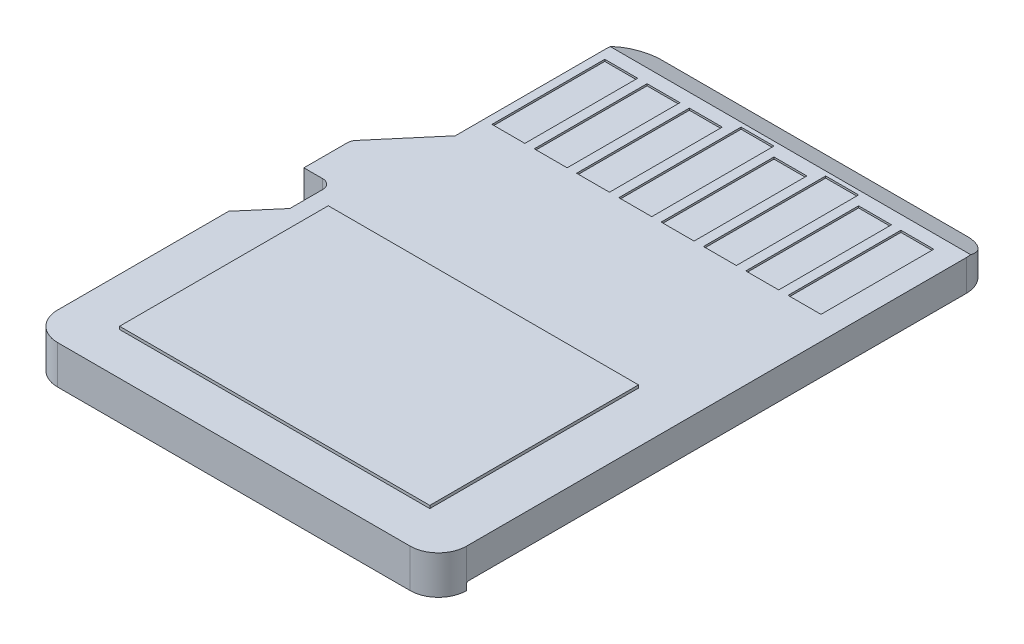
SolidWorks part; units mm, degrees
ref_plane "Front Plane" through (0, 0, 0) normal (0, 0, 1) x (1, 0, 0)
ref_plane "Top Plane" through (0, 0, 0) normal (0, 1, 0) x (1, 0, 0)
ref_plane "Right Plane" through (0, 0, 0) normal (1, 0, 0) x (0, 0, -1)
ref_plane "Plane1" through (1.2954, 0, 0) normal (-1, 0, 0) x (0, -1, 0)
sketch "Sketch1" plane through (1.2954, 0, 0) normal (-1, 0, 0) x (0, -1, 0)
  line L0 (-0.8382, 0) -> (-0.8382, -14.3917)
  line L1 (-0.8382, -14.3917) -> (-0.5842, -15.0267)
  line L2 (-0.5842, -15.0267) -> (0, -15.0267)
  line L3 (0, -15.0267) -> (0, 0)
  line L4 (0, 0) -> (-0.8382, 0)
extrude "Boss-Extrude1" add sketch "Sketch1" against normal blind 9.7536
sketch "Sketch2" plane through (1.2954, 0, 0) normal (-1, 0, 0) x (0, 0, 1)
  line L0 (0, 0) -> (-8.6868, 0)
  line L1 (-8.6868, 0) -> (-8.6868, 0.8382)
  line L2 (-8.6868, 0.8382) -> (0, 0.8382)
  line L3 (0, 0.8382) -> (0, 0)
extrude "Boss-Extrude2" add sketch "Sketch2" along normal blind 1.2954
sketch "Sketch3" plane through (0, 0, 0) normal (0, -1, 0) x (1, 0, 0)
  line L0 (0, -0.762) -> (0, 0)
  line L1 (0, 0) -> (11.049, 0)
  line L2 (11.049, 0) -> (11.049, -0.762)
  arc A0 (11.049, -0.762) -> (0, -0.762) centre (5.5245, 14.8745) cw
extrude "Boss-Extrude3" add sketch "Sketch3" along normal blind 0.2032
sketch "Sketch4" plane through (0, 0.8382, 0) normal (0, 1, 0) x (-1, 0, 0)
  line L0 (0, -5.3848) -> (-0.762, -5.3848)
  line L1 (-0.762, -5.3848) -> (-0.762, -7.4168)
  line L2 (-0.762, -7.4168) -> (0, -7.4168)
  line L3 (0, -7.4168) -> (0, -5.3848)
extrude "Cut-Extrude1" cut sketch "Sketch4" against normal through all
sketch "Sketch5" plane through (0, 0.8382, 0) normal (0, 1, 0) x (-1, 0, 0)
  line L0 (-1.2926, -1.143) -> (-1.2926, -6.7818)
  line L1 (-1.2926, -6.7818) -> (-9.6746, -6.7818)
  line L2 (-9.6746, -6.7818) -> (-9.6746, -1.143)
  line L3 (-9.6746, -1.143) -> (-1.2926, -1.143)
extrude "Boss-Extrude4" add sketch "Sketch5" along normal blind 0.0762
sketch "Sketch6" plane through (0, 0.8382, 0) normal (0, 1, 0) x (-1, 0, 0)
  line L0 (-2.413, -14.0208) -> (-1.524, -14.0208)
  line L1 (-1.524, -14.0208) -> (-1.524, -10.9728)
  line L2 (-1.524, -10.9728) -> (-2.413, -10.9728)
  line L3 (-2.413, -10.9728) -> (-2.413, -14.0208)
extrude "Cut-Extrude2" cut sketch "Sketch6" against normal blind 0.0508
sketch "Sketch7" plane through (0, 0.8382, 0) normal (0, 1, 0) x (-1, 0, 0)
  line L0 (-4.699, -14.0208) -> (-3.81, -14.0208)
  line L1 (-3.81, -14.0208) -> (-3.81, -10.9728)
  line L2 (-3.81, -10.9728) -> (-4.699, -10.9728)
  line L3 (-4.699, -10.9728) -> (-4.699, -14.0208)
extrude "Cut-Extrude3" cut sketch "Sketch7" against normal blind 0.0508
sketch "Sketch8" plane through (0, 0.8382, 0) normal (0, 1, 0) x (-1, 0, 0)
  line L0 (-2.667, -10.9728) -> (-3.556, -10.9728)
  line L1 (-3.556, -10.9728) -> (-3.556, -14.0208)
  line L2 (-3.556, -14.0208) -> (-2.667, -14.0208)
  line L3 (-2.667, -14.0208) -> (-2.667, -10.9728)
extrude "Cut-Extrude4" cut sketch "Sketch8" against normal blind 0.0508
sketch "Sketch9" plane through (0, 0.8382, 0) normal (0, 1, 0) x (-1, 0, 0)
  line L0 (-10.414, -10.9728) -> (-10.414, -14.0208)
  line L1 (-10.414, -14.0208) -> (-9.525, -14.0208)
  line L2 (-9.525, -14.0208) -> (-9.525, -10.9728)
  line L3 (-9.525, -10.9728) -> (-10.414, -10.9728)
extrude "Cut-Extrude5" cut sketch "Sketch9" against normal blind 0.0508
sketch "Sketch10" plane through (0, 0.8382, 0) normal (0, 1, 0) x (-1, 0, 0)
  line L0 (-6.985, -14.0208) -> (-6.096, -14.0208)
  line L1 (-6.096, -14.0208) -> (-6.096, -10.9728)
  line L2 (-6.096, -10.9728) -> (-6.985, -10.9728)
  line L3 (-6.985, -10.9728) -> (-6.985, -14.0208)
extrude "Cut-Extrude6" cut sketch "Sketch10" against normal blind 0.0508
sketch "Sketch11" plane through (0, 0.8382, 0) normal (0, 1, 0) x (-1, 0, 0)
  line L0 (-5.842, -10.9728) -> (-5.842, -14.2748)
  line L1 (-5.842, -14.2748) -> (-4.953, -14.2748)
  line L2 (-4.953, -14.2748) -> (-4.953, -10.9728)
  line L3 (-4.953, -10.9728) -> (-5.842, -10.9728)
extrude "Cut-Extrude7" cut sketch "Sketch11" against normal blind 0.0508
sketch "Sketch12" plane through (0, 0.8382, 0) normal (0, 1, 0) x (-1, 0, 0)
  line L0 (-7.239, -10.9728) -> (-8.128, -10.9728)
  line L1 (-8.128, -10.9728) -> (-8.128, -14.2748)
  line L2 (-8.128, -14.2748) -> (-7.239, -14.2748)
  line L3 (-7.239, -14.2748) -> (-7.239, -10.9728)
extrude "Cut-Extrude8" cut sketch "Sketch12" against normal blind 0.0508
sketch "Sketch13" plane through (0, 0.8382, 0) normal (0, 1, 0) x (-1, 0, 0)
  line L0 (-8.382, -10.9728) -> (-9.271, -10.9728)
  line L1 (-9.271, -10.9728) -> (-9.271, -14.0208)
  line L2 (-9.271, -14.0208) -> (-8.382, -14.0208)
  line L3 (-8.382, -14.0208) -> (-8.382, -10.9728)
extrude "Cut-Extrude9" cut sketch "Sketch13" against normal blind 0.0508
draft "Draft1" type of draft neutral plane draft angle 49.399 faces to draft 1 face at (0.381, 0.4191, -5.3848) neutral plane through (0, 0, 0) neutral plane normal (-1, 0, 0) parameters "D1"=49.399
draft "Draft2" type of draft neutral plane draft angle 49.635 faces to draft 1 face at (0.3239, 0.5239, -8.6868) neutral plane through (0, 0, 0) neutral plane normal (-1, 0, 0) parameters "D1"=49.635
fillet "Fillet2" radius 0.0508 1 edges
fillet "Fillet3" radius 0.254 2 edges at (0.762, 0.4191, -7.4168) (0, 0.4191, -8.6868)
fillet "Fillet4" radius 0.762 4 edges at (0, 0.3175, 0) (11.049, 0.2921, -15.0267) (11.049, 0.3175, 0) (1.2954, 0.2921, -15.0267)
